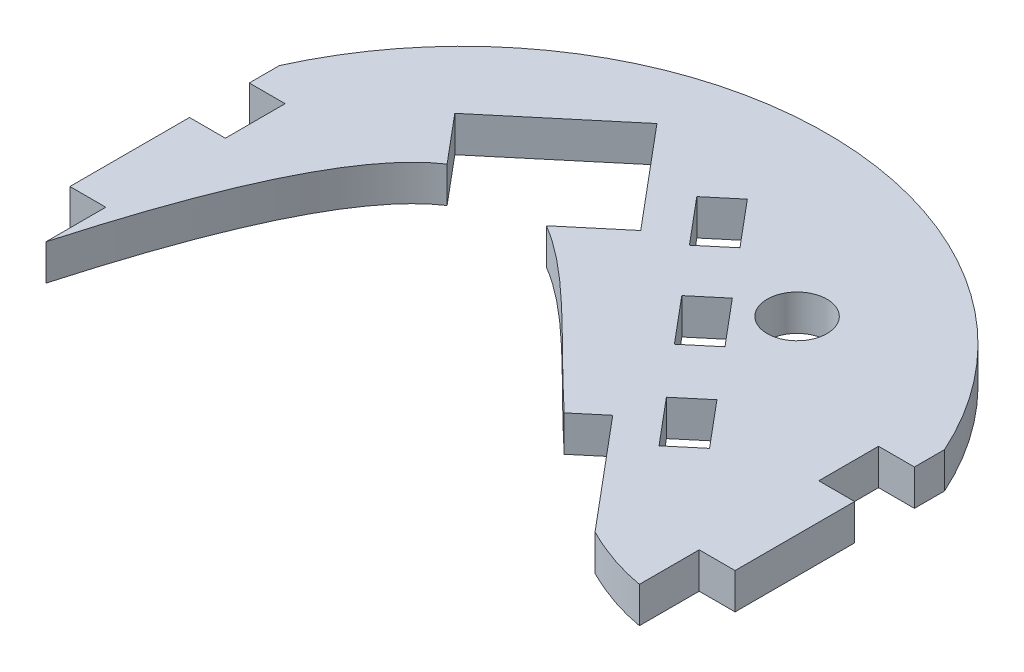
SolidWorks part; units mm, degrees
ref_plane "Alzado" through (0, 0, 0) normal (0, 0, 1) x (1, 0, 0)
ref_plane "Planta" through (0, 0, 0) normal (0, 1, 0) x (1, 0, 0)
ref_plane "Vista lateral" through (0, 0, 0) normal (1, 0, 0) x (0, 0, -1)
sketch "Croquis1" plane through (0, 0, 0) normal (0, 1, 0) x (1, 0, 0)
  circle A0 centre (0, 0) radius 30.5
extrude "Saliente-Extruir1" add sketch "Croquis1" along normal blind 3
sketch "Croquis2" plane through (0, 3, 0) normal (0, 1, 0) x (1, 0, 0)
  circle A0 centre (0, 0) radius 2
extrude "Cortar-Extruir1" cut sketch "Croquis2" against normal blind 4
sketch "Croquis5" plane through (0, 3, 0) normal (0, 1, 0) x (1, 0, 0)
  line L0 (0, 0) -> (0, 10)
  line L1 (28.8141, -5) -> (30.0874, -5)
  line L2 (28.8141, 5) -> (30.0874, 5)
  line L3 (-24.8141, 10) -> (-28.8141, 10)
  line L4 (24.8141, -5) -> (24.8141, -10)
  line L5 (-24.8141, -10) -> (-28.8141, -10)
  line L6 (24.8141, -5) -> (28.8141, -5)
  line L7 (24.8141, 5) -> (24.8141, 10)
  line L8 (-24.8141, 5) -> (-28.8141, 5)
  line L9 (-24.8141, 5) -> (-24.8141, 10)
  line L10 (-24.8141, -5) -> (-28.8141, -5)
  line L11 (-24.8141, -5) -> (-24.8141, -10)
  line L12 (24.8141, 5) -> (28.8141, 5)
  line L13 (24.8141, -10) -> (28.8141, -10)
  line L14 (24.8141, 10) -> (28.8141, 10)
  line L15 (-28.8141, 5) -> (-30.0874, 5)
  line L16 (-28.8141, -5) -> (-30.0874, -5)
  circle A1 centre (0, 0) radius 30.5 construction
  arc A2 (-28.8141, 10) -> (-30.0874, 5) centre (0, 0) ccw
  arc A3 (28.8141, 10) -> (28.8141, -10) centre (0, 0) cw
  arc A4 (-30.0874, -5) -> (-28.8141, -10) centre (0, 0) ccw
  arc A5 (30.0874, -5) -> (28.8141, -10) centre (0, 0) cw
  arc A6 (28.8141, 10) -> (30.0874, 5) centre (0, 0) cw
extrude "Cortar-Extruir3" cut sketch "Croquis5" against normal blind 4
sketch "Croquis7" plane through (0, 3, 0) normal (0, 1, 0) x (1, 0, 0)
  line L0 (-8.1011, 29.1011) -> (9.5756, 8.0348)
  line L1 (-1.4002, 16.4481) -> (-0.7574, 15.682)
  line L2 (-8.1011, 29.1011) -> (-27.2522, 13.0314)
  line L3 (27.2522, -13.0314) -> (8.1011, -29.1011)
  line L4 (8.1011, -29.1011) -> (-27.2522, 13.0314)
  line L5 (1.4284, 22.4114) -> (-0.8697, 20.4831)
  line L6 (1.4284, 22.4114) -> (4.6423, 18.5812)
  line L7 (4.6423, 18.5812) -> (2.3442, 16.6528)
  line L8 (2.3442, 16.6528) -> (-0.8697, 20.4831)
  line L9 (-24.8141, -10) -> (-28.8141, -10)
  line L10 (24.8141, -10) -> (28.8141, -10)
  line L11 (9.5756, 8.0348) -> (18.4139, -2.4983)
  line L12 (18.4139, -2.4983) -> (27.2522, -13.0314)
  line L13 (11.4555, 1.1272) -> (19.169, -8.0653)
  line L14 (19.169, -8.0653) -> (9.9765, -15.7788)
  line L15 (9.9765, -15.7788) -> (2.263, -6.5863)
  line L16 (11.4555, 1.1272) -> (2.263, -6.5863)
  line L17 (-1.4002, 16.4481) -> (-7.8281, 24.1085)
  line L18 (-1.4002, 16.4481) -> (-10.5927, 8.7346)
  line L19 (-10.5927, 8.7346) -> (-17.0206, 16.3951)
  line L20 (-7.8281, 24.1085) -> (-17.0206, 16.3951)
  line L21 (16.2929, 4.6967) -> (14.6859, 6.6118)
  line L22 (16.2929, 4.6967) -> (17.8998, 2.7815)
  line L23 (14.6859, 6.6118) -> (12.3878, 4.6834)
  line L24 (17.8998, 2.7815) -> (15.6017, 0.8532)
  line L25 (15.6017, 0.8532) -> (12.3878, 4.6834)
  line L26 (-0.7574, 15.682) -> (-5.0494, 12.0807)
  arc A1 (-28.8141, -10) -> (28.8141, -10) centre (0, 0) ccw
  spline S0 degree 3 poles (24.8141, -10) (2.6081, -6.0995) (-10.3265, 41.1093) (-24.8141, -10) knots 0 0 0 0 1 1 1 1
  point P7 (-9.5756, -8.0348)
extrude "Cortar-Extruir5" cut sketch "Croquis7" against normal blind 4
sketch "Croquis9" plane through (0, 3, 0) normal (0, 1, 0) x (1, 0, 0)
  line L0 (-8.3073, 29.3469) -> (22.8679, -7.8063)
  line L2 (7.9714, 14.6138) -> (11.1854, 10.7835)
  line L3 (-8.3073, 29.3469) -> (-21.7131, 18.0981)
  line L4 (-21.7131, 18.0981) -> (9.4621, -19.0551)
  line L5 (9.4621, -19.0551) -> (22.8679, -7.8063)
  line L6 (11.1854, 10.7835) -> (8.8872, 8.8552)
  line L7 (7.9714, 14.6138) -> (5.6733, 12.6854)
  arc A1 (28.8141, 10) -> (-28.8141, 10) centre (0, 0) ccw construction
extrude "Cortar-Extruir6" cut sketch "Croquis9" against normal blind 10 contours L2 L7 L0 L6
sketch "Croquis10" plane through (0, 3, 0) normal (0, 1, 0) x (1, 0, 0)
  line L0 (0, 0) -> (12, 0)
  line L1 (12, 0) -> (12, 16)
  circle A0 centre (12, 16) radius 2.5
extrude "Cortar-Extruir7" cut sketch "Croquis10" against normal blind 3
sketch "Croquis11" plane through (0, 3, 0) normal (0, 1, 0) x (1, 0, 0)
  line L0 (-24.8141, 10) -> (-27.8141, 10)
  line L1 (-24.8141, 10) -> (-28.8141, 10) construction
  line L2 (-27.8141, 10) -> (-27.8141, 12.5151)
  line L3 (-24.8141, 5) -> (-27.8141, 5)
  line L4 (-24.8141, 5) -> (-30.0874, 5) construction
  line L5 (-27.8141, 5) -> (-27.8141, -5)
  line L6 (-24.8141, -5) -> (-30.0874, -5) construction
  line L7 (24.8141, 10) -> (27.8141, 10)
  line L8 (24.8141, 10) -> (28.8141, 10) construction
  line L9 (27.8141, 10) -> (27.8141, 12.5151)
  line L10 (24.8141, 5) -> (27.8141, 5)
  line L11 (24.8141, 5) -> (30.0874, 5) construction
  line L12 (27.8141, 5) -> (27.8141, -5)
  line L13 (24.8141, -5) -> (30.0874, -5) construction
  arc A0 (28.8141, 10) -> (-28.8141, 10) centre (0, 0) ccw construction
  line M20 (24.8141, -5) -> (30.0874, -5)
  arc M21 (30.0874, -5) -> (30.0874, 5) centre (0, 0) ccw
  line M22 (30.0874, 5) -> (24.8141, 5)
  line M24 (24.8141, 10) -> (28.8141, 10)
  arc M25 (28.8141, 10) -> (-28.8141, 10) centre (0, 0) ccw
  line M26 (-28.8141, 10) -> (-24.8141, 10)
  line M28 (-24.8141, 5) -> (-30.0874, 5)
  arc M29 (-30.0874, 5) -> (-30.0874, -5) centre (0, 0) ccw
  line M30 (-30.0874, -5) -> (-24.8141, -5)
extrude "Cortar-Extruir8" cut sketch "Croquis11" against normal through all and the other way through all contours L12 M22 M20 M21 | L9 M24 M25 | L5 M28 M29 M30 | L2 M26 M25
